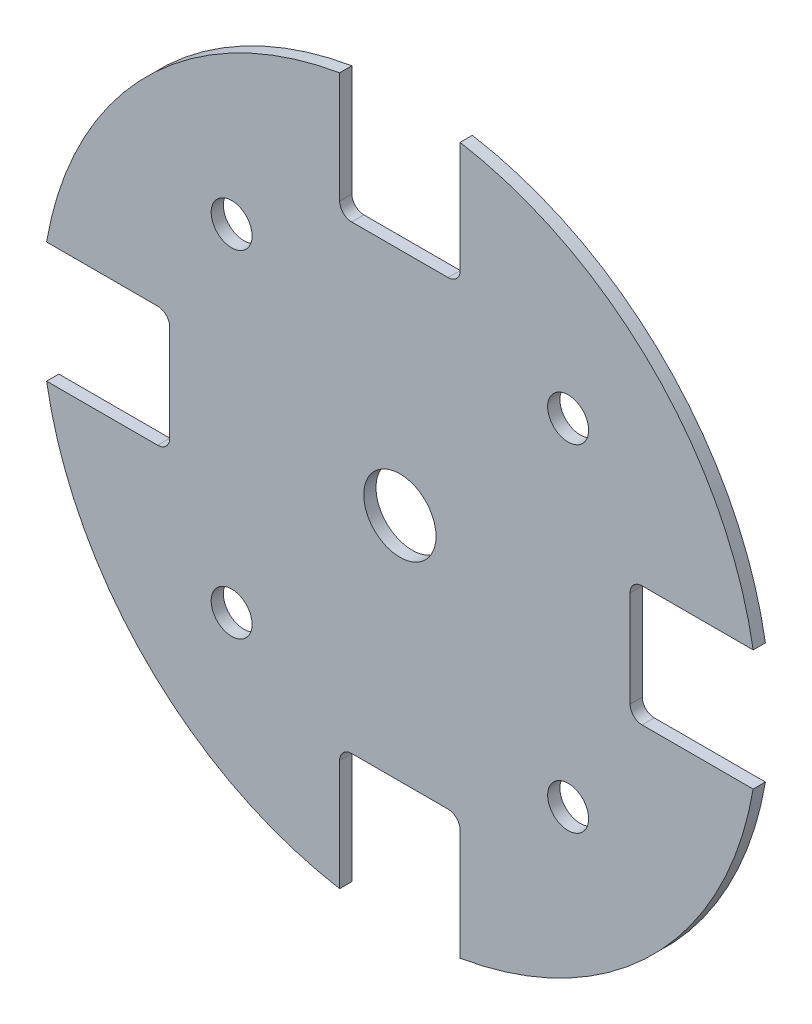
SolidWorks part; units mm, degrees
ref_plane "Front Plane" through (0, 0, 0) normal (0, 0, 1) x (1, 0, 0)
ref_plane "Top Plane" through (0, 0, 0) normal (0, 1, 0) x (1, 0, 0)
ref_plane "Right Plane" through (0, 0, 0) normal (1, 0, 0) x (0, 0, -1)
sketch "Sketch1" plane through (0, 0, 0) normal (0, 0, 1) x (1, 0, 0)
  line L0 (-29.3268, 5) -> (-20.1066, 5)
  line L1 (-29.3268, -5) -> (-20.1066, -5)
  line L2 (29.3268, 5) -> (20.1066, 5)
  line L3 (29.3268, -5) -> (20.1066, -5)
  line L4 (0, 0) -> (19.75, 0) construction
  line L5 (19.1066, 4) -> (19.1066, -4)
  line L6 (-19.1066, 4) -> (-19.1066, -4)
  line L7 (13.9654, 13.9654) -> (0, 0) construction
  line L8 (5, 29.3268) -> (5, 20.1066)
  line L9 (4, 19.1066) -> (-4, 19.1066)
  line L10 (-5, 29.3268) -> (-5, 20.1066)
  line L11 (5, -29.3268) -> (5, -20.1066)
  line L12 (4, -19.1066) -> (-4, -19.1066)
  line L13 (-5, -29.3268) -> (-5, -20.1066)
  line L14 (0, 0) -> (19.1066, 4) construction
  line L15 (0, 0) -> (4, -19.1066) construction
  arc A0 (29.3268, 5) -> (5, 29.3268) centre (0, 0) ccw
  circle A1 centre (0, 0) radius 19.75 construction
  arc A2 (-29.3268, -5) -> (-5, -29.3268) centre (0, 0) ccw
  arc A3 (20.1066, 5) -> (19.1066, 4) centre (20.1066, 4) ccw
  arc A4 (20.1066, -5) -> (19.1066, -4) centre (20.1066, -4) cw
  arc A5 (-20.1066, -5) -> (-19.1066, -4) centre (-20.1066, -4) ccw
  arc A6 (-20.1066, 5) -> (-19.1066, 4) centre (-20.1066, 4) cw
  circle A7 centre (13.9654, 13.9654) radius 1.7
  circle A8 centre (13.9654, -13.9654) radius 1.7
  circle A9 centre (-13.9654, -13.9654) radius 1.7
  circle A10 centre (-13.9654, 13.9654) radius 1.7
  circle A11 centre (0, 0) radius 3
  arc A12 (5, 20.1066) -> (4, 19.1066) centre (4, 20.1066) cw
  arc A13 (-5, 20.1066) -> (-4, 19.1066) centre (-4, 20.1066) ccw
  arc A14 (5, -20.1066) -> (4, -19.1066) centre (4, -20.1066) ccw
  arc A15 (-5, -20.1066) -> (-4, -19.1066) centre (-4, -20.1066) cw
  arc A16 (-5, 29.3268) -> (-29.3268, 5) centre (0, 0) ccw
  arc A17 (5, -29.3268) -> (29.3268, -5) centre (0, 0) ccw
  point P14 (19.1066, 5)
  point P17 (19.1066, -5)
  point P20 (-19.1066, -5)
  point P23 (-19.1066, 5)
  point P35 (0, 0)
  dimension "D1" = 59.5
  dimension "D2" = 39.5
  dimension "D4" = 1
  dimension "D8" = 6
  dimension "D3" = 10
  dimension "D6" = 45
  dimension "D10" = 90
  dimension "D7" = 4
  dimension "D9" = 2
extrude "Boss-Extrude1" add sketch "Sketch1" along normal blind 1.016
equation "\"D\" = 59.5"
equation "\"D1@Sketch1\"=\"D\""
equation "\"D2@Sketch1\"=\"D\"-20"
